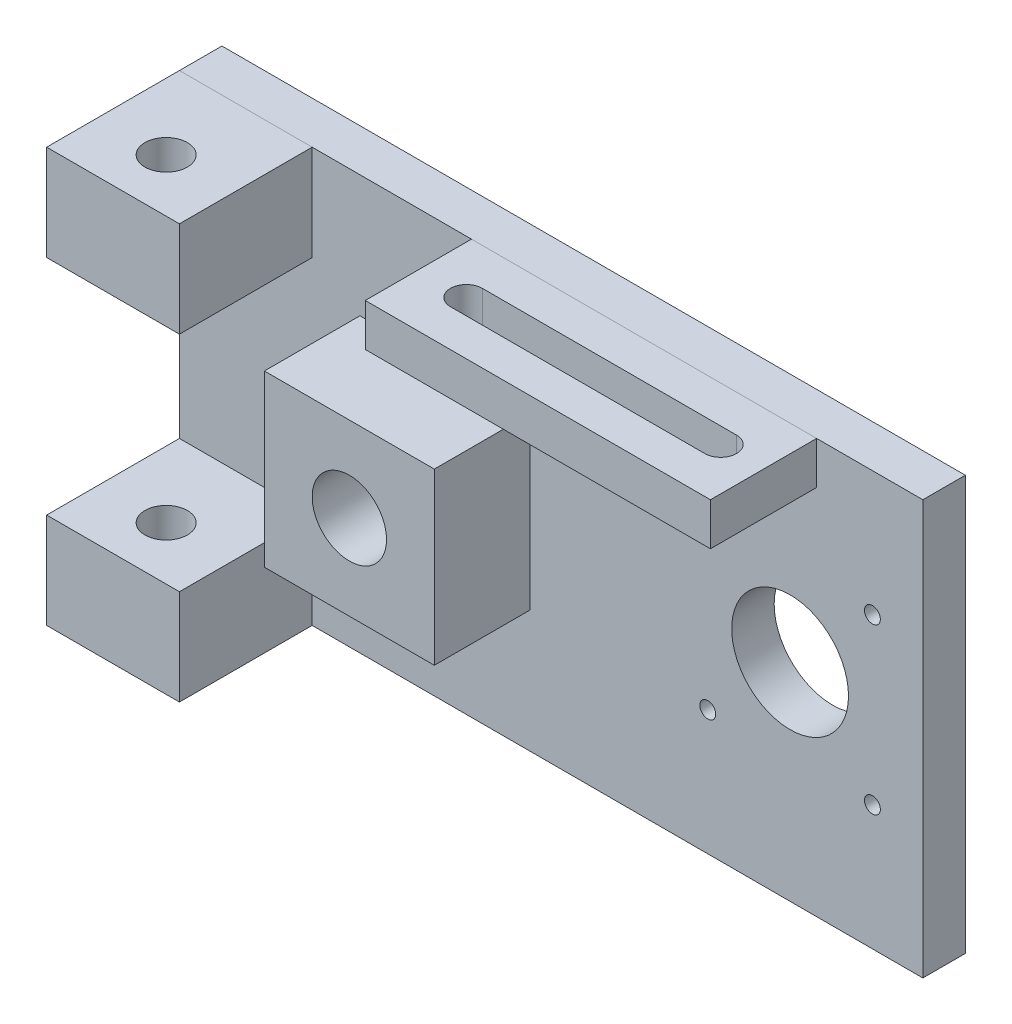
SolidWorks part; units mm, degrees
ref_plane "Front Plane" through (0, 0, 0) normal (0, 0, 1) x (1, 0, 0)
ref_plane "Top Plane" through (0, 0, 0) normal (0, 1, 0) x (1, 0, 0)
ref_plane "Right Plane" through (0, 0, 0) normal (1, 0, 0) x (0, 0, -1)
sketch "Sketch1" plane through (0, 0, 0) normal (0, 0, 1) x (1, 0, 0)
  line L1 (-70, -39) -> (70, -39)
  line L2 (-70, -39) -> (-70, 39)
  line L3 (-70, 39) -> (70, 39)
  line L4 (70, -39) -> (70, 39)
  line L5 (-70, -39) -> (70, 39) construction
  line L6 (-70, 39) -> (70, -39) construction
  point P0 (0, 0)
  dimension "D1" = 140
  dimension "D2" = 78
extrude "Boss-Extrude1" add sketch "Sketch1" along normal blind 8
sketch "Sketch2" plane through (0, 0, 8) normal (0, 0, 1) x (1, 0, 0)
  line L0 (70, 39) -> (-70, 39) construction
  line L1 (29.5, -15.5) -> (60.5, -15.5) construction
  line L2 (29.5, -15.5) -> (29.5, 15.5) construction
  line L3 (29.5, 15.5) -> (60.5, 15.5) construction
  line L4 (60.5, -15.5) -> (60.5, 15.5) construction
  line L5 (29.5, -15.5) -> (60.5, 15.5) construction
  line L6 (29.5, 15.5) -> (60.5, -15.5) construction
  line L7 (70, -39) -> (70, 39) construction
  line L8 (-70, 39) -> (-70, -39) construction
  circle A4 centre (29.5, 15.5) radius 1.5
  circle A5 centre (60.5, 15.5) radius 1.5
  circle A6 centre (60.5, -15.5) radius 1.5
  circle A7 centre (29.5, -15.5) radius 1.5
  circle A8 centre (-20, 0) radius 11
  circle A9 centre (45, 0) radius 11
  point P0 (45, 0)
  dimension "D1" = 31
  dimension "D2" = 31
  dimension "D3" = 3
  dimension "D4" = 3
  dimension "D5" = 3
  dimension "D6" = 3
  dimension "D9" = 22
  dimension "D11" = 50
  dimension "D12" = 22
  dimension "D7" = 39
  dimension "D8" = 25
  dimension "D10" = 39
extrude "Cut-Extrude1" cut sketch "Sketch2" against normal up to next
sketch "Sketch3" plane through (0, 0, 8) normal (0, 0, 1) x (1, 0, 0)
  line L0 (70, 39) -> (-70, 39) construction
  line L1 (-70, 39) -> (-45, 39)
  line L2 (-70, 39) -> (-70, 21)
  line L3 (-70, 21) -> (-45, 21)
  line L4 (-45, 39) -> (-45, 21)
  line L5 (-70, -39) -> (-45, -39)
  line L6 (-70, -39) -> (-70, -21)
  line L7 (-70, -21) -> (-45, -21)
  line L8 (-45, -39) -> (-45, -21)
  line L9 (-25, 39) -> (0, 39)
  line L10 (-25, 39) -> (-25, 31)
  line L11 (-25, 31) -> (0, 31)
  line L12 (0, 39) -> (0, 31)
  line M14 (70, 39) -> (-70, 39)
  line M15 (-70, 39) -> (-70, -39)
  line M16 (-70, -39) -> (70, -39)
  dimension "D1" = 18
  dimension "D2" = 25
  dimension "D3" = 25
  dimension "D4" = 18
  dimension "D5" = 25
  dimension "D6" = 8
  dimension "D7" = 20
extrude "Boss-Extrude2" add sketch "Sketch3" along normal blind 25 separate body contours L4 L3 M14 M15 | L8 L7 M16 M15
sketch "Sketch4" plane through (0, 39, 0) normal (0, 1, 0) x (1, 0, 0)
  line L0 (-70, -33) -> (-70, -8) construction
  line L4 (-45, -33) -> (-70, -33) construction
  circle A1 centre (-57.5, -23) radius 4
  dimension "D1" = 8
  dimension "D3" = 10
  dimension "D2" = 12.5
extrude "Cut-Extrude2" cut sketch "Sketch4" against normal through all
sketch "Sketch7" plane through (0, 0, 8) normal (0, 0, 1) x (1, 0, 0)
  line L1 (-36, -16) -> (-4, -16)
  line L2 (-36, -16) -> (-36, 16)
  line L3 (-36, 16) -> (-4, 16)
  line L4 (-4, -16) -> (-4, 16)
  line L5 (-36, -16) -> (-4, 16) construction
  line L6 (-36, 16) -> (-4, -16) construction
  circle A0 centre (-20, 0) radius 11 construction
  circle A1 centre (-20, 0) radius 11
  point P0 (-20, 0)
  dimension "D1" = 32
  dimension "D2" = 32
extrude "Boss-Extrude4" add sketch "Sketch7" along normal blind 8 contours L3 L4 L1 L2
sketch "Sketch8" plane through (0, 0, 16) normal (0, 0, 1) x (1, 0, 0)
  line L4 (-4, -16) -> (-4, 16)
  line L5 (-4, 16) -> (-36, 16)
  line L6 (-36, 16) -> (-36, -16)
  line L7 (-36, -16) -> (-4, -16)
  line L8 (-4, -16) -> (-4, 16)
  line L9 (-4, 16) -> (-36, 16)
  line L10 (-36, 16) -> (-36, -16)
  line L11 (-36, -16) -> (-4, -16)
  circle A2 centre (-20, 0) radius 7
  circle A3 centre (-20, 0) radius 7
  dimension "D1" = 0
  dimension "D2" = 4
extrude "Boss-Extrude5" add sketch "Sketch8" along normal blind 10
sketch "Sketch9" plane through (0, 0, 8) normal (0, 0, 1) x (1, 0, 0)
  line L0 (70, 39) -> (-70, 39) construction
  line L5 (50, 39) -> (-15, 39)
  line L6 (50, 39) -> (50, 31)
  line L7 (50, 31) -> (-15, 31)
  line L8 (-15, 39) -> (-15, 31)
  line L9 (70, -39) -> (70, 39) construction
  dimension "D1" = 8
  dimension "D2" = 65
  dimension "D3" = 20
extrude "Boss-Extrude6" add sketch "Sketch9" along normal blind 20 separate body
sketch "Sketch11" plane through (0, 39, 0) normal (0, 1, 0) x (1, 0, 0)
  line L0 (50, -28) -> (-15, -28) construction
  line L1 (-5.9602, -15) -> (41.9237, -15)
  line L2 (-5.9602, -21) -> (41.9237, -21)
  circle A0 centre (-5.9602, -18) radius 3
  circle A1 centre (41.9237, -18) radius 3
  dimension "D1" = 6
  dimension "D2" = 6
  dimension "D3" = 10
  dimension "D4" = 10
extrude "Cut-Extrude3" cut sketch "Sketch11" against normal up to next (8 mm away) contours A0 | A1 L1 A0 L2 | A1
